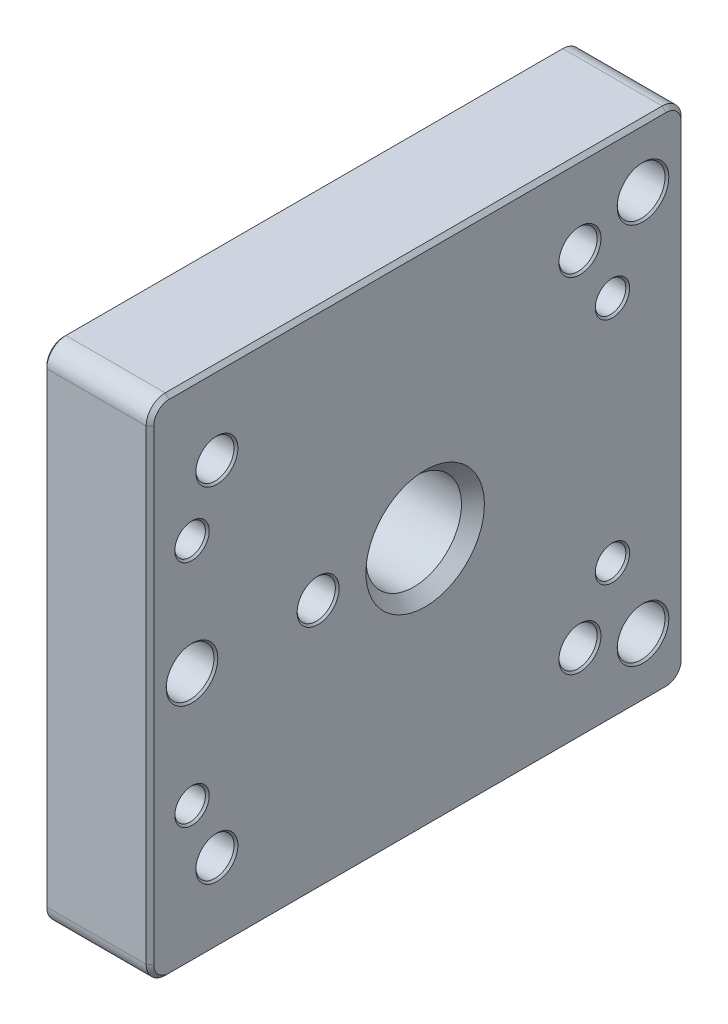
SolidWorks part; units mm, degrees
ref_plane "Спереди" through (0, 0, 0) normal (0, 0, 1) x (1, 0, 0)
ref_plane "Сверху" through (0, 0, 0) normal (0, 1, 0) x (1, 0, 0)
ref_plane "Справа" through (0, 0, 0) normal (1, 0, 0) x (0, 0, -1)
ref_plane "Плоскость4" through (0, 0, 0) normal (-1, 0, 0) x (0, -1, 0)
sketch "Эскиз1" plane through (0, 0, 0) normal (-1, 0, 0) x (0, -1, 0)
  line L0 (-13.2, 14) -> (-13.2, -14)
  line L1 (-13.2, -14) -> (13.2, -14)
  line L2 (13.2, -14) -> (13.2, 14)
  line L3 (13.2, 14) -> (-13.2, 14)
extrude "Бобышка-Вытянуть1" add sketch "Эскиз1" against normal blind 5.5
hole_wizard "Диаметр отверстия Ø1.6 (1.6)1" positions "Эскиз3" profile "Эскиз2" hole size "Ø1.6" standard "Ansi Metric"
sketch "Эскиз3" plane through (0, 0, 0) normal (-1, 0, 0) x (0, 0, 1)
  point P0 (-10.2, -6)
  point P1 (11.8, -6)
  point P2 (11.8, 6)
sketch "Эскиз2" plane through (0, -6, -10.2) normal (0, 1, 0) x (0, 0, 1)
  line L0 (0, 0) -> (0, 5.5)
  line L1 (0, 5.5) -> (0.8, 5.5)
  line L2 (0.8, 5.5) -> (0.8, 0)
  line L5 (0.8, 0) -> (0, 0)
  line L11 (0, -6.35) -> (0, 107.95) construction
  dimension "Диаметр сквозного отверстия" = 1.6
  dimension "Глубина сквозного отверстия" = 5.5
hole_wizard "Диаметр отверстия Ø2.5 (2.5)1" positions "Эскиз5" profile "Эскиз4" hole size "Ø2.5" standard "Ansi Metric"
sketch "Эскиз5" plane through (5.5, 0, 0) normal (1, 0, 0) x (0, 0, -1)
  point P0 (11.8, -10)
sketch "Эскиз4" plane through (5.5, -10, -11.8) normal (0, 1, 0) x (0, 0, -1)
  line L0 (0, 0) -> (0, 5.5)
  line L1 (0, 5.5) -> (1.25, 5.5)
  line L2 (1.25, 5.5) -> (1.25, 0)
  line L5 (1.25, 0) -> (0, 0)
  line L11 (0, -6.35) -> (0, 107.95) construction
  dimension "Диаметр сквозного отверстия" = 2.5
  dimension "Глубина сквозного отверстия" = 5.5
hole_wizard "Диаметр отверстия Ø1.6 (1.6)2" positions "Эскиз7" profile "Эскиз6" hole size "Ø1.6" standard "Ansi Metric"
sketch "Эскиз7" plane through (5.5, 0, 0) normal (1, 0, 0) x (0, 0, -1)
  point P0 (10.2, 6)
sketch "Эскиз6" plane through (5.5, 6, -10.2) normal (0, 1, 0) x (0, 0, -1)
  line L0 (0, 0) -> (0, 5.5)
  line L1 (0, 5.5) -> (0.8, 5.5)
  line L2 (0.8, 5.5) -> (0.8, 0)
  line L5 (0.8, 0) -> (0, 0)
  line L11 (0, -6.35) -> (0, 107.95) construction
  dimension "Диаметр сквозного отверстия" = 1.6
  dimension "Глубина сквозного отверстия" = 5.5
hole_wizard "Диаметр отверстия Ø2.5 (2.5)2" positions "Эскиз9" profile "Эскиз8" hole size "Ø2.5" standard "Ansi Metric"
sketch "Эскиз9" plane through (0, 0, 0) normal (-1, 0, 0) x (0, 0, 1)
  point P0 (-11.8, 10)
  point P1 (11.8, 0)
sketch "Эскиз8" plane through (0, 10, -11.8) normal (0, 1, 0) x (0, 0, 1)
  line L0 (0, 0) -> (0, 5.5)
  line L1 (0, 5.5) -> (1.25, 5.5)
  line L2 (1.25, 5.5) -> (1.25, 0)
  line L5 (1.25, 0) -> (0, 0)
  line L11 (0, -6.35) -> (0, 107.95) construction
  dimension "Диаметр сквозного отверстия" = 2.5
  dimension "Глубина сквозного отверстия" = 5.5
hole_wizard "Диаметр отверстия Ø5.0 (5)1" positions "Эскиз11" profile "Эскиз10" hole size "Ø5.0" standard "Ansi Metric"
sketch "Эскиз11" plane through (5.5, 0, 0) normal (1, 0, 0) x (0, 0, -1)
  point P0 (0.4, 0)
sketch "Эскиз10" plane through (5.5, 0, -0.4) normal (0, 1, 0) x (0, 0, -1)
  line L0 (0, 0) -> (0, 5.5)
  line L1 (0, 5.5) -> (2.5, 5.5)
  line L2 (2.5, 5.5) -> (2.5, 0)
  line L5 (2.5, 0) -> (0, 0)
  line L11 (0, -6.35) -> (0, 107.95) construction
  dimension "Диаметр сквозного отверстия" = 5
  dimension "Глубина сквозного отверстия" = 5.5
hole_wizard "Цековка для винта с внутренним шестигранником M1.61" positions "Эскиз13" profile "Эскиз12" counterbore size "M1.6" standard "Ansi Metric"
sketch "Эскиз13" plane through (0, 0, 0) normal (-1, 0, 0) x (0, 0, 1)
  point P0 (-8.5, 9)
  point P1 (-8.5, -9)
  point P2 (5.2, 0)
  point P3 (10.5, -9)
  point P4 (10.5, 9)
sketch "Эскиз12" plane through (0, 9, -8.5) normal (0, 1, 0) x (0, 0, 1)
  line L0 (0, 0) -> (0, 5.5)
  line L1 (0, 5.5) -> (1, 5.5)
  line L3 (1, 5.5) -> (1, 3.5)
  line L4 (1, 3.5) -> (1.6, 3.5)
  line L5 (1.6, 3.5) -> (1.6, 0)
  line L7 (1.6, 0) -> (0, 0)
  line L11 (0, -6.35) -> (0, 107.95) construction
  dimension "Диаметр сквозного отверстия" = 2
  dimension "Глубина сквозного отверстия" = 5.5
  dimension "Диаметр цековки" = 3.2
  dimension "Глубина цековки" = 3.5
fillet "Скругление1" radius 1 4 edges at (2.75, 13.2, 14) (2.75, 13.2, -14) (2.75, -13.2, -14) (2.75, -13.2, 14)
chamfer "Фаска1" distance 0.6 angle 45 2 edges at (0, 0, -2.9) (5.5, 0, -2.9)
chamfer "Фаска2" distance 0.1 angle 45 37 edges at (5.5, -6, 12.6) (5.5, 10, -10.55) (0, -12.9071, 13.7071) (0, 0, 14) (0, -13.2, 0) (0, 12.9071, 13.7071) (0, -12.9071, -13.7071) (0, 13.2, 0) (0, 0, -14) (0, 12.9071, -13.7071) (5.5, -6, -9.4) (0, 0, 6.8) (5.5, 9, -7.5) (5.5, 0, 6.2) (0, 10, -10.55) (5.5, 6, 12.6) (0, 6, -11) (3.5, 9, -7.5) (0, -10, -13.05) (0, -9, 12.1) (0, -6, -9.4) (5.5, 6, -11) (3.5, -9, -7.5) (5.5, -10, -13.05) (3.5, 0, 6.2) (5.5, -9, -7.5) (3.5, -9, 11.5) (5.5, -9, 11.5) (0, -6, 12.6) (5.5, 0, 13.05) (0, 0, 13.05) (5.5, 9, 11.5) (0, 6, 12.6) (3.5, 9, 11.5) (0, -9, -6.9) (0, 9, 12.1) (0, 9, -6.9)
chamfer "Фаска3" distance 0.2 angle 45 8 edges at (5.5, 0, -14) (5.5, -12.9071, -13.7071) (5.5, 12.9071, -13.7071) (5.5, -13.2, 0) (5.5, 13.2, 0) (5.5, -12.9071, 13.7071) (5.5, 12.9071, 13.7071) (5.5, 0, 14)
